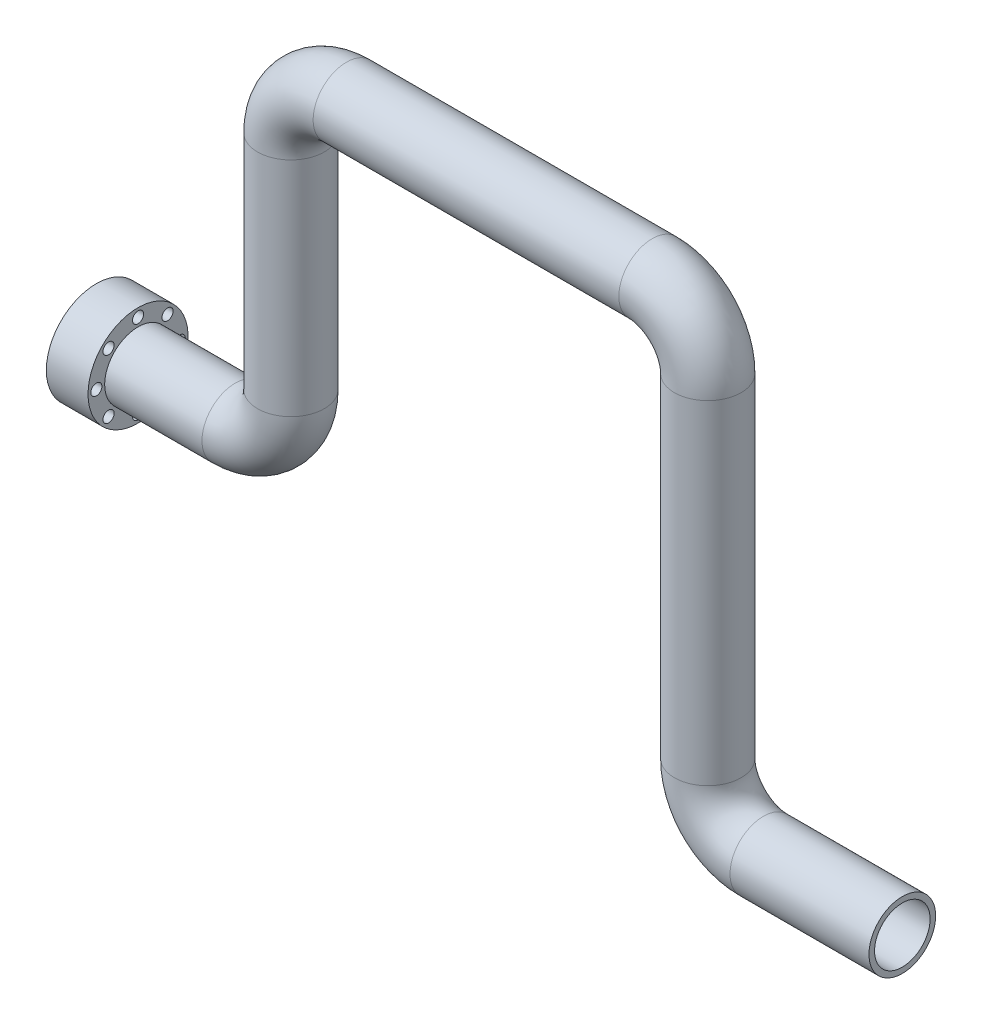
SolidWorks part; units mm, degrees
ref_plane "Front Plane" through (0, 0, 0) normal (0, 0, 1) x (1, 0, 0)
ref_plane "Top Plane" through (0, 0, 0) normal (0, 1, 0) x (1, 0, 0)
ref_plane "Right Plane" through (0, 0, 0) normal (1, 0, 0) x (0, 0, -1)
sketch "Sketch1" plane through (0, 0, 0) normal (0, 0, 1) x (1, 0, 0)
  line L0 (0, 0) -> (25, 0)
  line L1 (35, 10) -> (35, 50)
  line L2 (45, 60) -> (100, 60)
  line L3 (110, 50) -> (110, -10)
  line L4 (120, -20) -> (145, -20)
  arc A0 (120, -20) -> (110, -10) centre (120, -10) cw
  arc A1 (110, 50) -> (100, 60) centre (100, 50) ccw
  arc A2 (35, 50) -> (45, 60) centre (45, 50) cw
  arc A3 (35, 10) -> (25, 0) centre (25, 10) cw
  point P9 (110, -20)
  point P12 (110, 60)
  point P15 (35, 60)
  point P18 (35, 0)
  dimension "D6" = 10
  dimension "D1" = 35
  dimension "D2" = 75
  dimension "D3" = 60
  dimension "D4" = 35
  dimension "D5" = 80
sketch "Sketch2" plane through (0, 0, 0) normal (1, 0, 0) x (0, 0, -1)
  circle A0 centre (0, 0) radius 5
  circle A1 centre (0, 0) radius 6
  dimension "D1" = 10
  dimension "D2" = 12
sweep "Sweep1" add profiles "Sketch2" path "Sketch1"
sketch "Sketch3" plane through (0, 0, 0) normal (-1, 0, 0) x (0, 0, 1)
  circle A0 centre (0, 0) radius 6
  circle A1 centre (0, 0) radius 9
  dimension "D1" = 12
  dimension "D2" = 18
extrude "Boss-Extrude1" add sketch "Sketch3" against normal blind 7.5 separate body
sketch "Sketch4" plane through (0, 0, 0) normal (-1, 0, 0) x (0, 0, 1)
  line L0 (0, 9) -> (0, -9) construction
  circle A0 centre (0, 0) radius 7.5
  circle A1 centre (0, 0) radius 9 construction
  circle A2 centre (0, 7.5) radius 1
  circle A3 centre (5.3033, 5.3033) radius 1
  circle A4 centre (0, 0) radius 7.5
  circle A5 centre (7.5, 0) radius 1
  circle A6 centre (0, 0) radius 7.5
  circle A7 centre (5.3033, -5.3033) radius 1
  circle A8 centre (0, 0) radius 7.5
  circle A9 centre (0, -7.5) radius 1
  circle A10 centre (0, 0) radius 7.5
  circle A11 centre (-5.3033, -5.3033) radius 1
  circle A12 centre (0, 0) radius 7.5
  circle A13 centre (-7.5, 0) radius 1
  circle A14 centre (0, 0) radius 7.5
  circle A15 centre (-5.3033, 5.3033) radius 1
  circle A16 centre (0, 0) radius 7.5
  point P34 (0, 0)
  dimension "D1" = 15
  dimension "D2" = 2
  dimension "D3" = 8
extrude "Cut-Extrude1" cut sketch "Sketch4" against normal blind 10 contours A3 | A5 | A2 | A15 | A11 | A7 | A13 | A9
